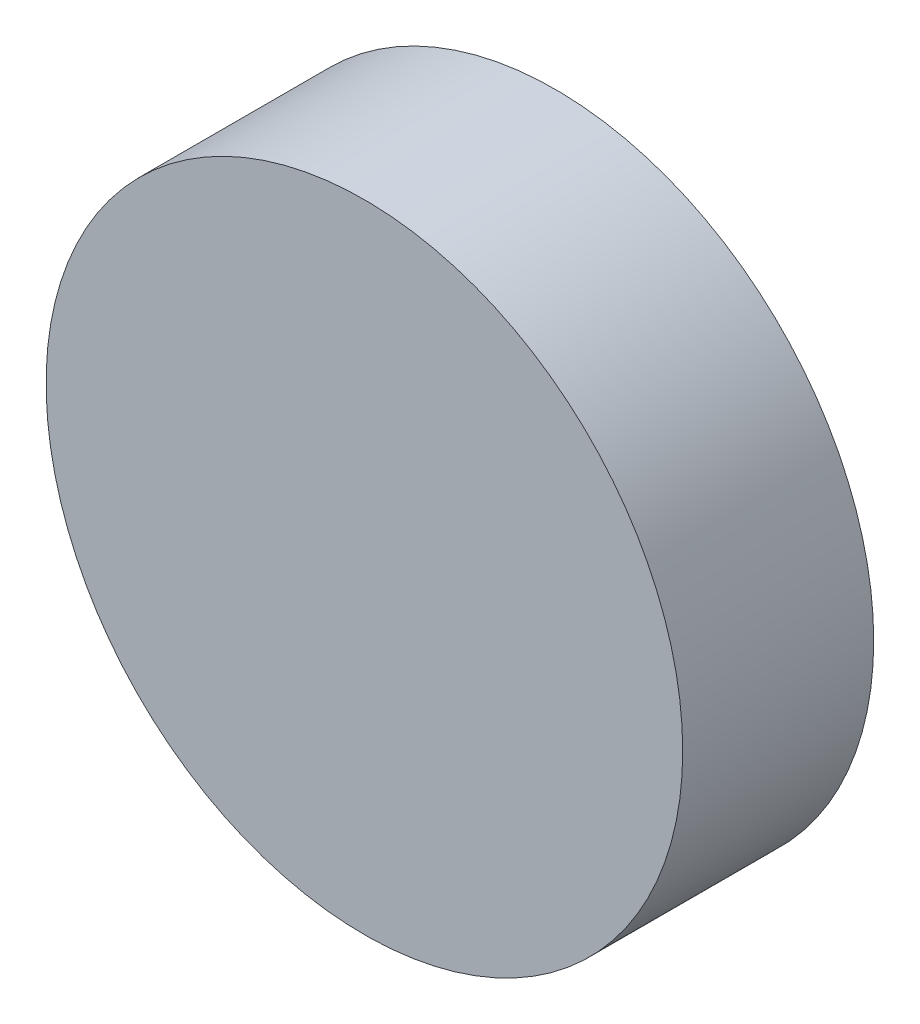
SolidWorks part; units mm, degrees
ref_plane "Front Plane" through (0, 0, 0) normal (1, 0, 0) x (0, 1, 0)
ref_plane "Top Plane" through (0, 0, 0) normal (0, 0, 1) x (0, 1, 0)
ref_plane "Right Plane" through (0, 0, 0) normal (0, 1, 0) x (-1, 0, 0)
sketch "Sketch1" plane through (0, 0, 0) normal (0, 0, 1) x (0, 1, 0)
  circle A0 centre (0, 0) radius 95.25
  dimension "D1" = 190.5
extrude "Boss-Extrude1" add sketch "Sketch1" along normal mid plane 57.15
